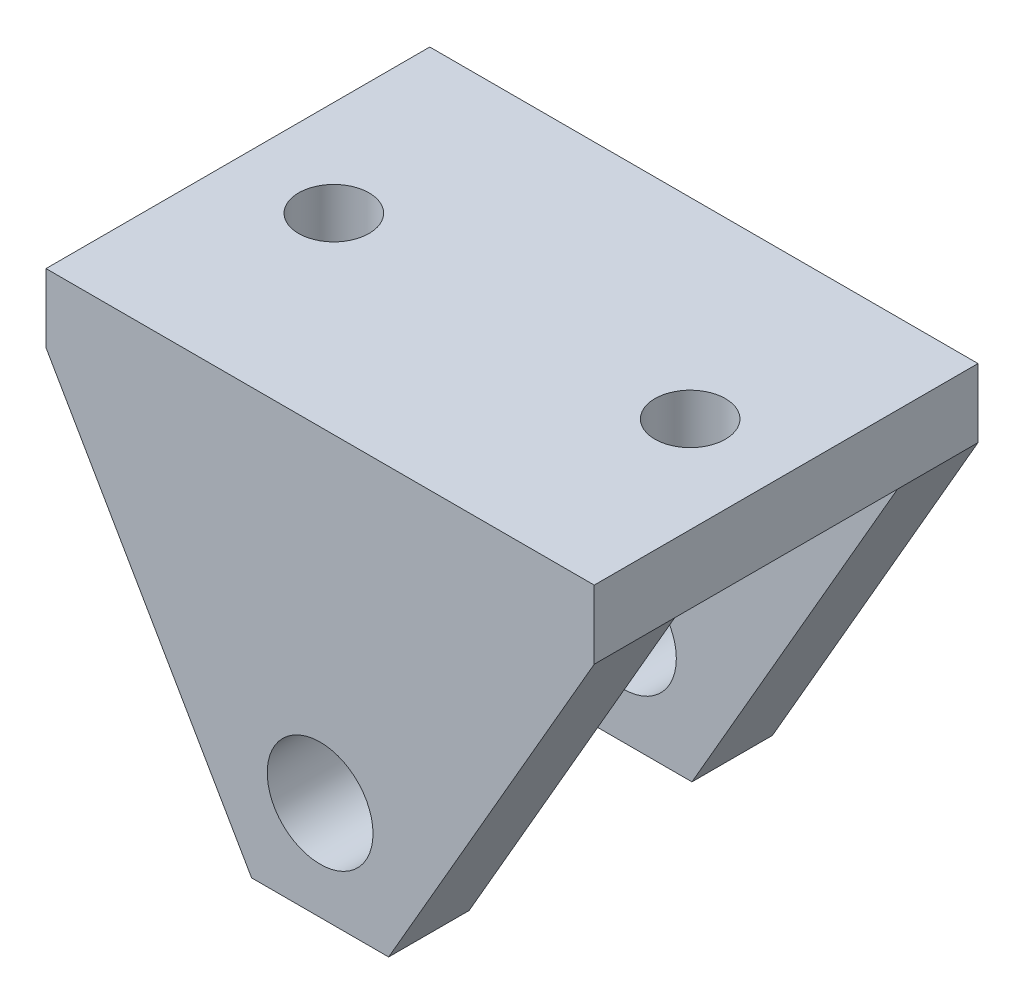
SolidWorks part; units mm, degrees
material "6061-T6 (SS)"
ref_plane "Front Plane" through (0, 0, 0) normal (0, 0, 1) x (1, 0, 0)
ref_plane "Top Plane" through (0, 0, 0) normal (0, 1, 0) x (1, 0, 0)
ref_plane "Right Plane" through (0, 0, 0) normal (1, 0, 0) x (0, 0, -1)
sketch "Sketch2" plane through (0, 0, 0) normal (0, 1, 0) x (1, 0, 0)
  line L0 (0, 0) -> (0, 13.439) construction
  line L1 (0, 0) -> (15.2263, 0) construction
  line L3 (-25.4, 17.78) -> (25.4, 17.78)
  line L4 (-25.4, 17.78) -> (-25.4, -17.78)
  line L5 (-25.4, -17.78) -> (25.4, -17.78)
  line L6 (25.4, 17.78) -> (25.4, -17.78)
  circle A0 centre (-16.51, 0) radius 3.2639
  circle A2 centre (16.51, 0) radius 3.2639
  dimension "D5" = 6.5278
  dimension "D6" = 16.51
  dimension "D1" = 50.8
  dimension "D2" = 25.4
  dimension "D3" = 35.56
  dimension "D4" = 17.78
extrude "Boss-Extrude1" add sketch "Sketch2" against normal blind 39.37
sketch "Sketch4" plane through (0, 0, 17.78) normal (0, 0, 1) x (1, 0, 0)
  line L0 (-25.4, -6.35) -> (-6.35, -39.37)
  line L1 (-25.4, -39.37) -> (-25.4, 0) construction
  line L2 (-25.4, -39.37) -> (25.4, -39.37) construction
  line L3 (-6.35, -39.37) -> (-25.4, -39.37)
  line L4 (-25.4, -39.37) -> (-25.4, -6.35)
  line L5 (0, 0) -> (0, 16.2985) construction
  line L6 (-25.4, 0) -> (25.4, 0) construction
  line L7 (6.35, -39.37) -> (25.4, -39.37)
  line L8 (25.4, -6.35) -> (6.35, -39.37)
  line L9 (25.4, -39.37) -> (25.4, -6.35)
  circle A0 centre (0, -30.1968) radius 4.9022
  point P10 (0, 0)
  point P19 (0, 0)
  dimension "D3" = 9.8044
  dimension "D4" = 9.1732
  dimension "D1" = 6.35
  dimension "D2" = 6.35
extrude "Cut-Extrude1" cut sketch "Sketch4" against normal through all
sketch "Sketch5" plane through (0, -39.37, 0) normal (0, -1, 0) x (1, 0, 0)
  line L0 (-25.4, -17.78) -> (-25.4, 17.78) construction
  line L1 (-25.4, 10.3251) -> (25.4, 10.3251)
  line L2 (-25.4, 10.3251) -> (-25.4, -10.3251)
  line L3 (-25.4, -10.3251) -> (25.4, -10.3251)
  line L4 (25.4, 10.3251) -> (25.4, -10.3251)
  line L5 (25.4, -17.78) -> (25.4, 17.78) construction
  line L6 (0, 0) -> (0, 50000) construction
  line L7 (0, 0) -> (50000, 0) construction
  point P13 (25000, 0)
  dimension "D1" = 20.6502
  dimension "D2" = 10.3251
  dimension "D3" = 10.3251
extrude "Cut-Extrude2" cut sketch "Sketch5" against normal blind 33.02
